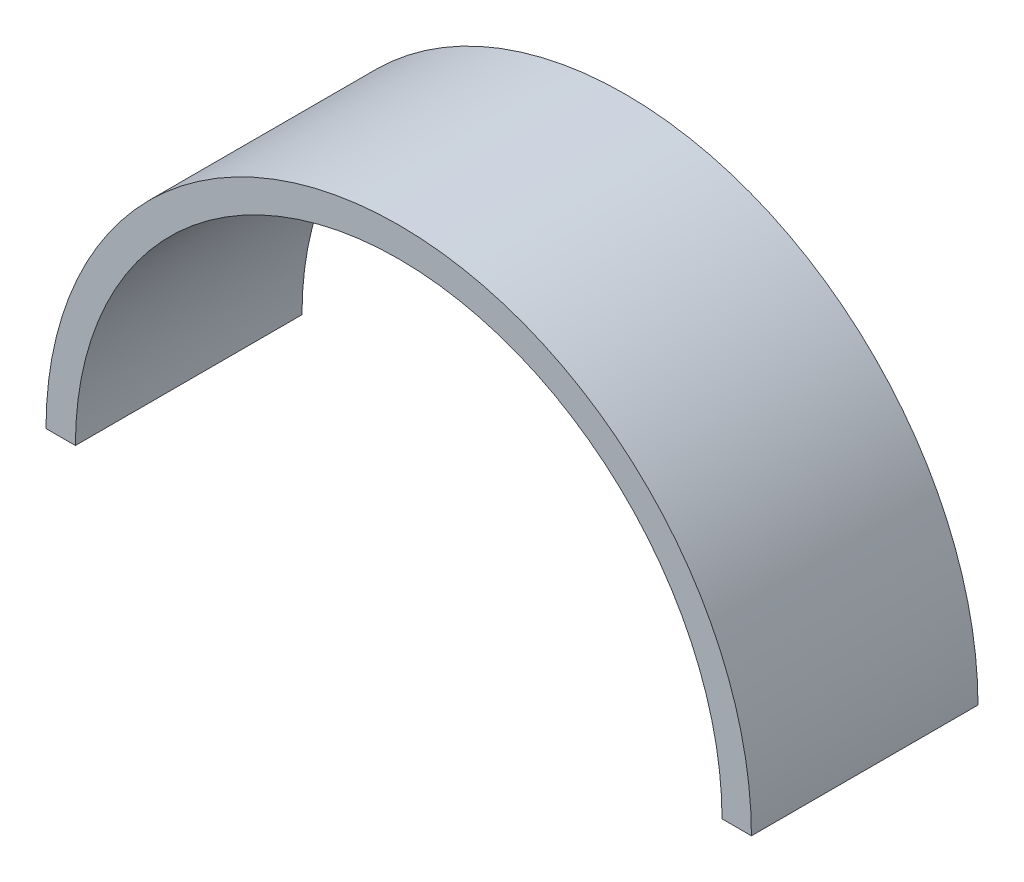
SolidWorks part; units mm, degrees
ref_plane "Alzado" through (0, 0, 0) normal (0, 0, 1) x (1, 0, 0)
ref_plane "Planta" through (0, 0, 0) normal (0, 1, 0) x (1, 0, 0)
ref_plane "Vista lateral" through (0, 0, 0) normal (1, 0, 0) x (0, 0, -1)
sketch "Croquis1" plane through (0, 0, 0) normal (0, 0, 1) x (1, 0, 0)
  line L0 (-26.4, 0) -> (-28.8, 0)
  line L1 (26.4, 0) -> (28.8, 0)
  arc A0 (28.8, 0) -> (-28.8, 0) centre (0, 0) ccw
  arc A1 (26.4, 0) -> (-26.4, 0) centre (0, 0) ccw
  dimension "D2" = 57.6
  dimension "D1" = 2.4
extrude "Saliente-Extruir1" add sketch "Croquis1" along normal blind 18.5
